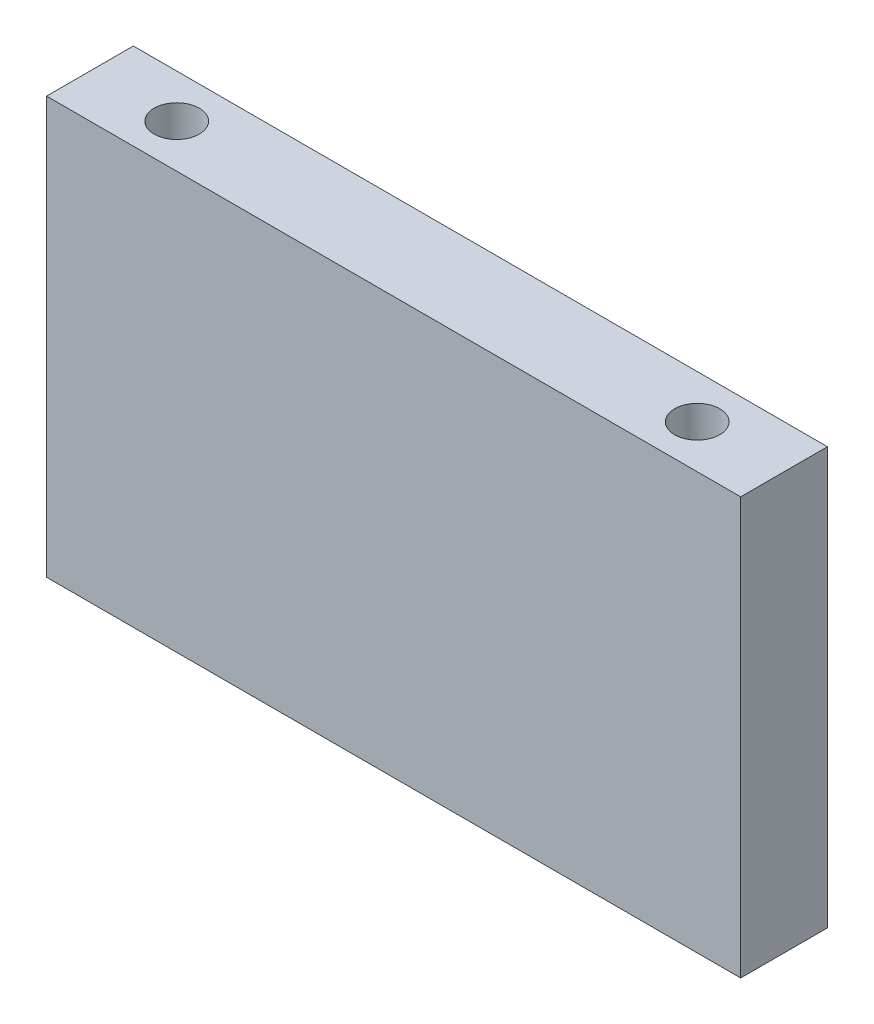
SolidWorks part; units mm, degrees
ref_plane "Front Plane" through (0, 0, 0) normal (0, 0, 1) x (1, 0, 0)
ref_plane "Top Plane" through (0, 0, 0) normal (0, 1, 0) x (1, 0, 0)
ref_plane "Right Plane" through (0, 0, 0) normal (1, 0, 0) x (0, 0, -1)
sketch "Sketch1" plane through (0, 0, 0) normal (0, 0, 1) x (1, 0, 0)
  line L1 (0, 0) -> (50.8, 0)
  line L2 (0, 0) -> (0, 30.5)
  line L3 (0, 30.5) -> (50.8, 30.5)
  line L4 (50.8, 0) -> (50.8, 30.5)
extrude "Boss-Extrude1" add sketch "Sketch1" along normal blind 6.35
sketch "Sketch2" plane through (0, 30.5, 0) normal (0, 1, 0) x (1, 0, 0)
  line L0 (50.8, -6.35) -> (0, -6.35) construction
  line L1 (0, -6.35) -> (0, 0) construction
  point P0 (6.35, -3.175)
  point P1 (44.45, -3.1819)
  point P2 (0, -3.175)
  dimension "D1" = 38.1
  dimension "D2" = 6.35
  dimension "D3" = 3.175
hole_wizard "M4x0.7 Tapped Hole1" positions "Sketch4" profile "Sketch3" tap size "M4x0.7" standard "ANSI Metric" end condition through all
sketch "Sketch4" plane through (0, 30.5, 0) normal (0, 1, 0) x (1, 0, 0)
  point P0 (6.35, -3.175)
  point P3 (44.45, -3.1819)
cosmetic thread "Hole Thread1" parameters "D2"=4
cosmetic thread "Hole Thread2" parameters "D2"=4
sketch "Sketch3" plane through (6.35, 30.5, 3.175) normal (1, 0, 0) x (0, 0, 1)
  line L0 (0, 0) -> (0, 30.5)
  line L1 (0, 30.5) -> (1.65, 30.5)
  line L2 (1.65, 30.5) -> (1.65, 0)
  line L5 (1.65, 0) -> (0, 0)
  line L11 (0, -6.35) -> (0, 107.95) construction
  dimension "Thru Tap Drill Dia." = 3.3
  dimension "Thru Tap Drill Depth" = 30.5
ref_plane "Plane1" through (0, 15.25, 0) normal (0, 1, 0) x (1, 0, 0)
